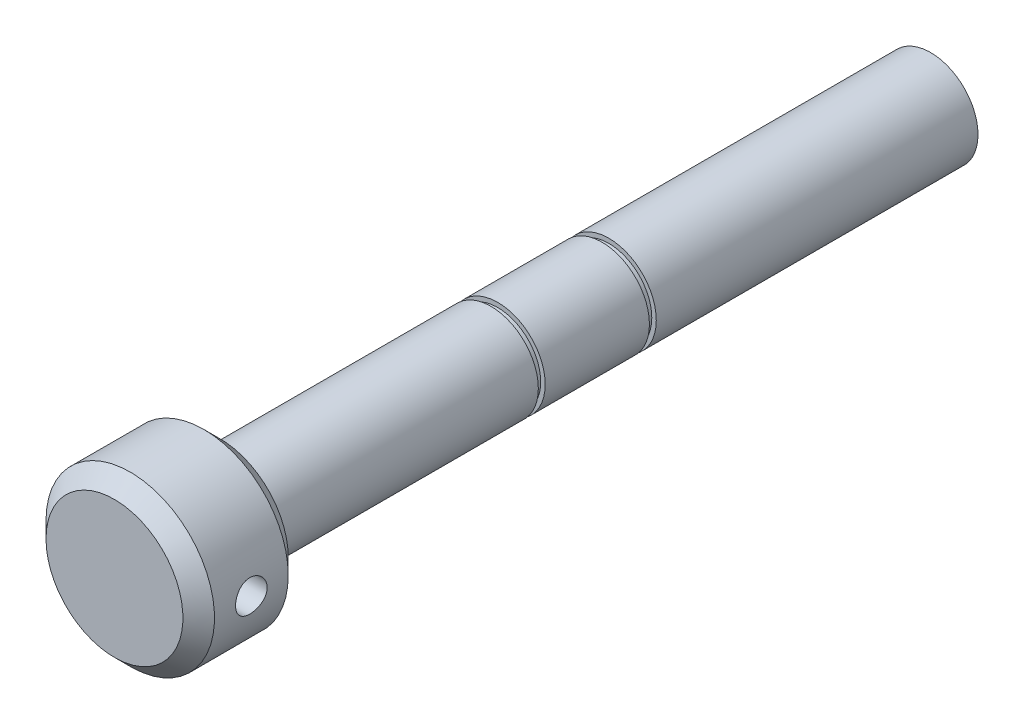
SolidWorks part; units mm, degrees
ref_plane "Piano frontale" through (0, 0, 0) normal (0, 0, 1) x (1, 0, 0)
ref_plane "Piano superiore" through (0, 0, 0) normal (0, 1, 0) x (1, 0, 0)
ref_plane "Piano destro" through (0, 0, 0) normal (1, 0, 0) x (0, 0, -1)
sketch "Schizzo1" plane through (0, 0, 0) normal (0, 0, 1) x (1, 0, 0)
  circle A0 centre (0, 0) radius 16
  dimension "D1" = 32
extrude "Estrusione-Estrusione1" add sketch "Schizzo1" along normal blind 20
chamfer "Smusso1" distance 3 angle 45 2 edges at (16, 0, 20) (16, 0, 0)
sketch "Schizzo2" plane through (0, 0, 0) normal (1, 0, 0) x (0, 0, -1)
  circle A0 centre (-10, 0) radius 3
  dimension "D2" = 6
  dimension "D1" = 10
extrude "Taglio-Estrusione1" cut sketch "Schizzo2" against normal through all both and the other way through all
sketch "Schizzo3" plane through (0, 0, 0) normal (0, 0, 1) x (1, 0, 0)
  circle A0 centre (0, 0) radius 9
  dimension "D1" = 18
extrude "Estrusione-Estrusione2" add sketch "Schizzo3" against normal blind 135
cosmetic thread "Filettatura cosmetica1" parameters "D2"=16.344
sketch "Schizzo4" plane through (0, 0, 0) normal (1, 0, 0) x (0, 0, -1)
  line L0 (51.5, 9) -> (51.5, 8.15)
  line L1 (135, 9) -> (0, 9) construction
  line L2 (51.5, 8.15) -> (52.8, 8.15)
  line L3 (52.8, 8.15) -> (52.8, 9)
  line L4 (52.8, 9) -> (51.5, 9)
  line L5 (72.6, 9) -> (72.6, 8.15)
  line L6 (72.6, 8.15) -> (73.9, 8.15)
  line L7 (73.9, 8.15) -> (73.9, 9)
  line L8 (73.9, 9) -> (72.6, 9)
  line L9 (-20, 13) -> (-20, -13) construction
  line L10 (0, 0) -> (137.4851, 0) construction
  line L11 (0, -13) -> (0, 13) construction
  dimension "D1" = 71.5
  dimension "D2" = 21.1
  dimension "D3" = 0.85
  dimension "D4" = 0.85
  dimension "D5" = 1.3
  dimension "D6" = 1.3
revolve "Taglia-Rivoluzione1" cut sketch "Schizzo4" angle 360 about L10
